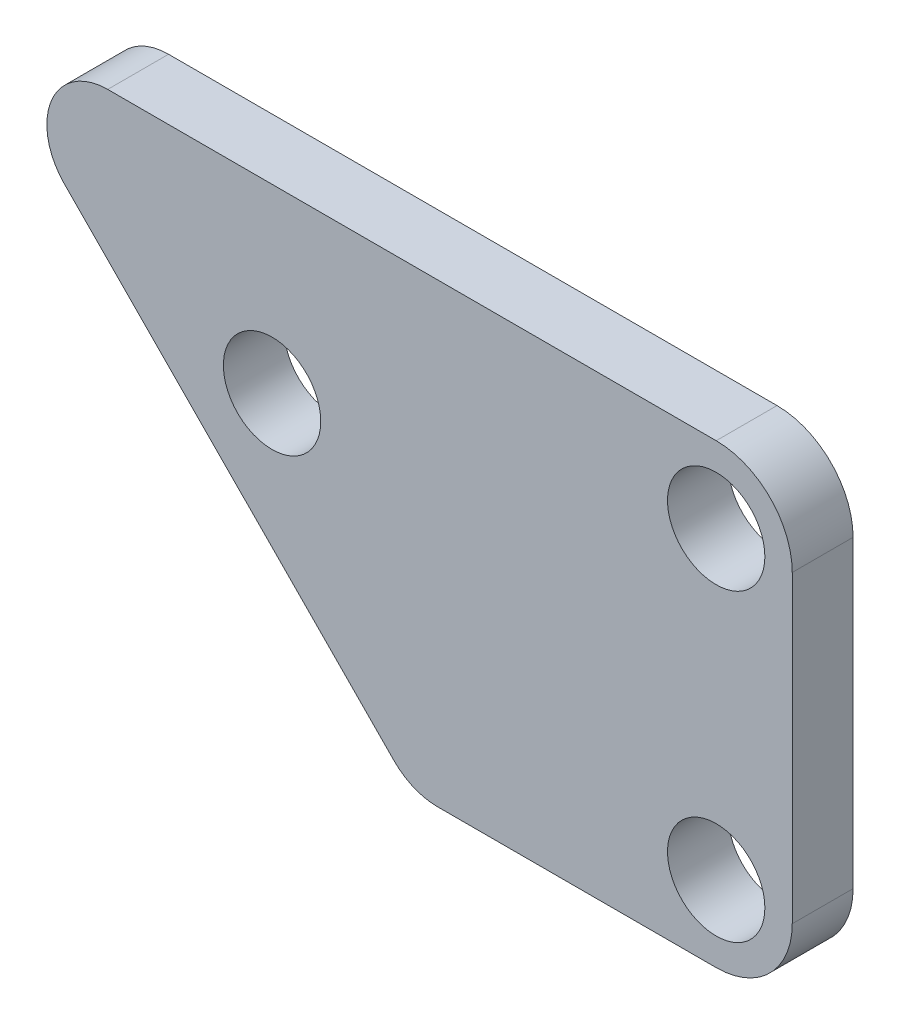
SolidWorks part; units mm, degrees
ref_plane "正面" through (0, 0, 0) normal (0, 0, 1) x (1, 0, 0)
ref_plane "平面" through (0, 0, 0) normal (0, 1, 0) x (1, 0, 0)
ref_plane "右側面" through (0, 0, 0) normal (1, 0, 0) x (0, 0, -1)
sketch "ｽｹｯﾁ1" plane through (0, 0, 0) normal (0, 0, 1) x (1, 0, 0)
  line L0 (2.5, 0) -> (2.5, -10)
  line L1 (0, 2.5) -> (-20, 2.5)
  line L2 (-21.4247, -0.9036) -> (-10.5875, -11.9036)
  line L3 (-9.1628, -12.5) -> (0, -12.5)
  circle A0 centre (0, 0) radius 1.6
  circle A1 centre (0, -10) radius 1.6
  circle A2 centre (-14.5979, -3.45) radius 1.6
  arc A3 (2.5, 0) -> (0, 2.5) centre (0, 0) ccw
  arc A4 (0, -12.5) -> (2.5, -10) centre (0, -10) ccw
  arc A5 (-9.1628, -12.5) -> (-10.5875, -11.9036) centre (-9.1628, -10.5) cw
  arc A6 (-20, 2.5) -> (-21.4247, -0.9036) centre (-20, 0.5) ccw
  point P6 (0, 0)
  point P7 (0, 0)
  point P16 (-10, -12.5)
  point P19 (-1.6542, 1.4697)
  point P20 (-15.6293, 0.2457)
  point P21 (0, 0)
  point P23 (0, 0)
  point P25 (-1.9901, 1.8631)
  dimension "D1" = 3.2
  dimension "D2" = 5
  dimension "D5" = 2
  dimension "D6" = 2
  dimension "D3" = 10
  dimension "D4" = 10
  dimension "D7" = 16
  dimension "D8" = 20
  dimension "D9" = 15
extrude "ﾎﾞｽ - 押し出し1" add sketch "ｽｹｯﾁ1" along normal blind 2
